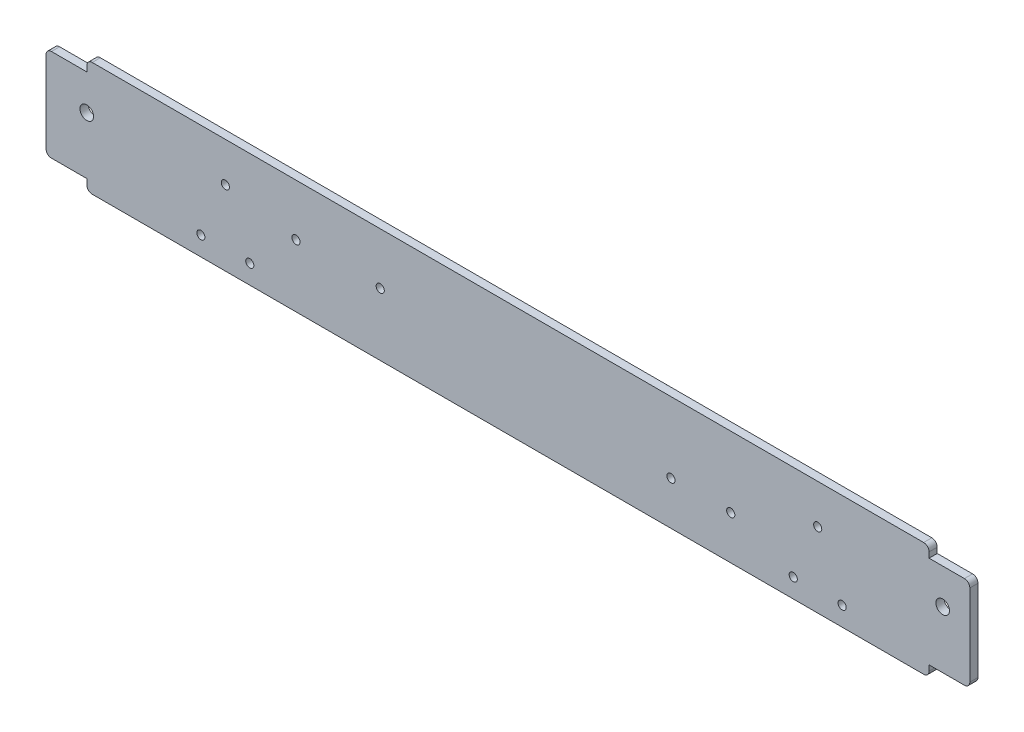
SolidWorks part; units mm, degrees
material "MDF"
ref_plane "Alzado" through (0, 0, 0) normal (0, 0, 1) x (1, 0, 0)
ref_plane "Planta" through (0, 0, 0) normal (0, 1, 0) x (1, 0, 0)
ref_plane "Vista lateral" through (0, 0, 0) normal (1, 0, 0) x (0, 0, -1)
sketch "Croquis1" plane through (0, 0, 0) normal (0, 0, 1) x (1, 0, 0)
  line L1 (-170, 21) -> (170, 21)
  line L2 (-170, 21) -> (-170, -21)
  line L3 (-170, -21) -> (170, -21)
  line L4 (170, 21) -> (170, -21)
  line L5 (-170, 21) -> (170, -21) construction
  line L6 (-170, -21) -> (170, 21) construction
  line L7 (105, -14) -> (123, -14) construction
  circle A1 centre (-47, 2) radius 1.5
  circle A2 centre (-78, 2) radius 1.5
  circle A3 centre (-104, 6.5) radius 1.5
  circle A4 centre (-113, -14) radius 1.5
  circle A5 centre (-95, -14) radius 1.5
  circle A7 centre (-155, 4) radius 2.5
  circle A9 centre (160, 4) radius 2.5
  circle A12 centre (114, 6.5) radius 1.5
  circle A13 centre (105, -14) radius 1.5
  circle A14 centre (123, -14) radius 1.5
  circle A15 centre (82, -5) radius 1.5
  circle A16 centre (60, -5) radius 1.5
  point P0 (0, 0)
  point P10 (114, -14)
  dimension "D9" = 3
  dimension "D11" = 23
  dimension "D23" = 5
  dimension "D19" = 5
  dimension "D1" = 42
  dimension "D6" = 16
  dimension "D7" = 88
  dimension "D8" = 340
  dimension "D10" = 23
  dimension "D12" = 31
  dimension "D13" = 92
  dimension "D14" = 27.5
  dimension "D15" = 66
  dimension "D16" = 7
  dimension "D17" = 18
  dimension "D18" = 57
  dimension "D20" = 25
  dimension "D24" = 10
  dimension "D25" = 25
  dimension "D27" = 27.5
  dimension "D28" = 56
  dimension "D29" = 18
  dimension "D30" = 7
  dimension "D32" = 22
  dimension "D21" = 15
extrude "Saliente-Extruir1" add sketch "Croquis1" along normal blind 3
sketch "Croquis2" plane through (0, 0, 3) normal (0, 0, 1) x (1, 0, 0)
  line L0 (-170, -17) -> (-155, -17)
  line L1 (-170, 21) -> (-170, -21) construction
  line L2 (-155, -17) -> (-155, -21)
  line L3 (-170, -21) -> (170, -21) construction
  line L4 (-170, -17) -> (-170, -21)
  line L5 (-170, -21) -> (-155, -21)
  dimension "D1" = 4
  dimension "D2" = 15
extrude "Cortar-Extruir2" cut sketch "Croquis2" against normal through all
mirror "Simetría4" about plane through (0, 0, 0) normal (1, 0, 0) of "Cortar-Extruir2" second plane through (0, 0, 0) second plane normal (0, 1, 0)
fillet "Redondeo1" radius 2 8 edges at (155, -21, 1.5) (170, 17, 1.5) (155, 21, 1.5) (-170, -17, 1.5) (-155, -21, 1.5) (-170, 17, 1.5) (-155, 21, 1.5) (170, -17, 1.5)
